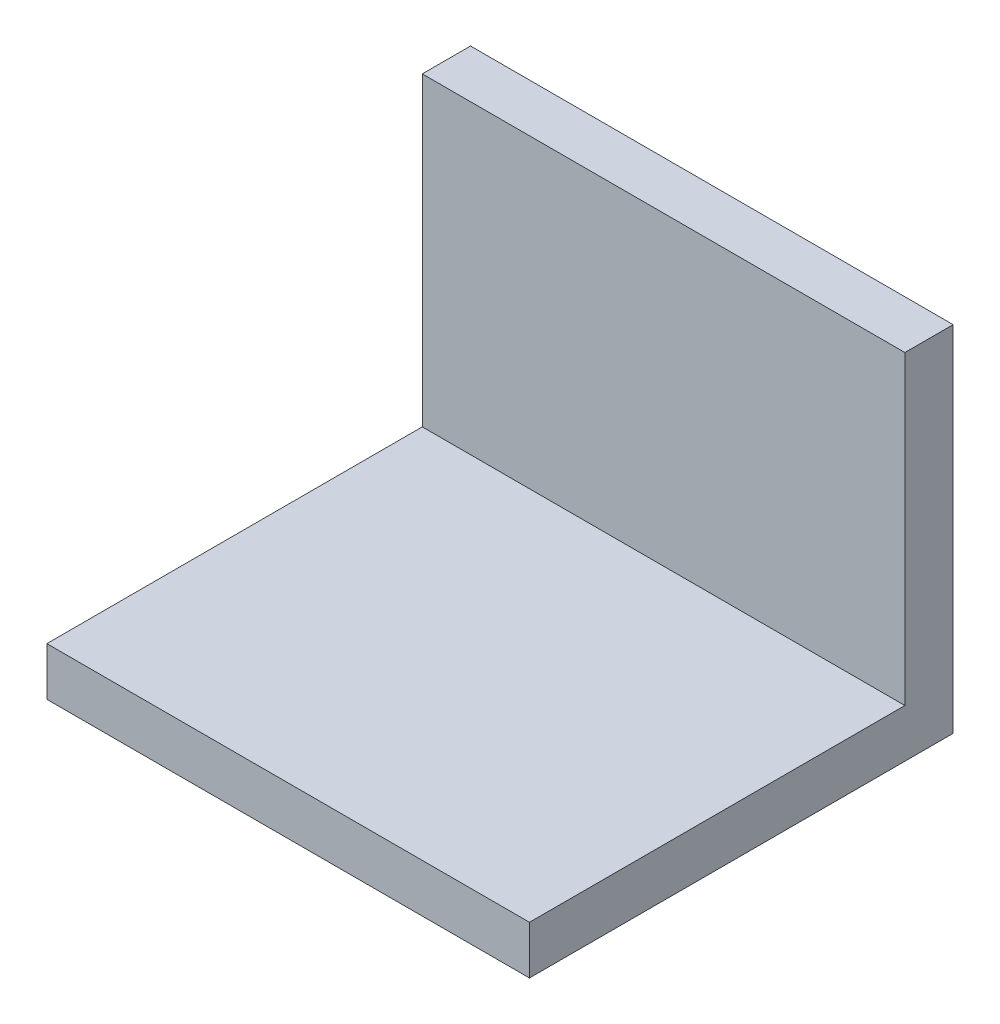
SolidWorks part; units mm, degrees
ref_plane "Front Plane" through (0, 0, 0) normal (0, 0, 1) x (1, 0, 0)
ref_plane "Top Plane" through (0, 0, 0) normal (0, 1, 0) x (1, 0, 0)
ref_plane "Right Plane" through (0, 0, 0) normal (1, 0, 0) x (0, 0, -1)
sketch "Sketch1" plane through (0, 0, 0) normal (1, 0, 0) x (0, 0, -1)
  line L0 (0, 0) -> (66.894, 0)
  line L1 (66.894, 0) -> (66.894, 55.8859)
  line L2 (66.894, 55.8859) -> (59.274, 55.8859)
  line L3 (59.274, 55.8859) -> (59.274, 7.62)
  line L4 (59.274, 7.62) -> (0, 7.62)
  line L5 (0, 7.62) -> (0, 0)
extrude "Extrude1" add sketch "Sketch1" against normal blind 76.2
ref_plane "Plane1" through (-6.35, 0, 0) normal (1, 0, 0) x (0, 0, -1)
